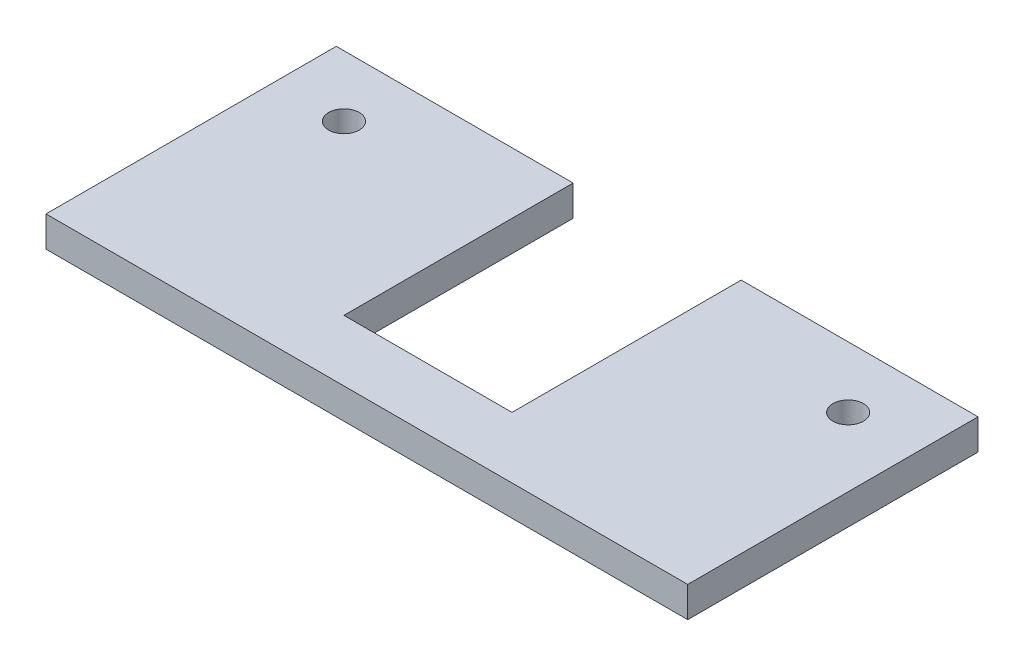
SolidWorks part; units mm, degrees
ref_plane "Спереди" through (0, 0, 0) normal (0, 0, 1) x (1, 0, 0)
ref_plane "Сверху" through (0, 0, 0) normal (0, 1, 0) x (1, 0, 0)
ref_plane "Справа" through (0, 0, 0) normal (1, 0, 0) x (0, 0, -1)
sketch "Эскиз1" plane through (0, 0, 0) normal (0, 1, 0) x (1, 0, 0)
  line L0 (0, 0) -> (33, 0) construction
  line L1 (16.5, 0) -> (11, 0) construction
  line L2 (16.5, 0) -> (22, 0) construction
  line L3 (11, 0) -> (11, -11)
  line L4 (11, -11) -> (22, -11)
  line L5 (22, -11) -> (22, 0)
  line L6 (11, 0) -> (11, 4)
  line L7 (11, 4) -> (22, 4) construction
  line L8 (22, 4) -> (22, 0)
  line L9 (16.5, -11) -> (16.5, -15) construction
  line L10 (-1, 0) -> (-4.5, 0) construction
  line L11 (34, 0) -> (37.5, 0) construction
  line L12 (11, 4) -> (-4.5, 4)
  line L13 (-4.5, 4) -> (-4.5, -15)
  line L14 (-4.5, -15) -> (37.5, -15)
  line L15 (37.5, -15) -> (37.5, 4)
  line L16 (37.5, 4) -> (22, 4)
  circle A0 centre (0, 0) radius 1
  circle A1 centre (33, 0) radius 1
  dimension "D1" = 2
  dimension "D2" = 33
  dimension "D3" = 5.5
  dimension "D4" = 11
  dimension "D5" = 4
  dimension "D6" = 4
  dimension "D7" = 3.5
extrude "Бобышка-Вытянуть1" add sketch "Эскиз1" along normal blind 2
